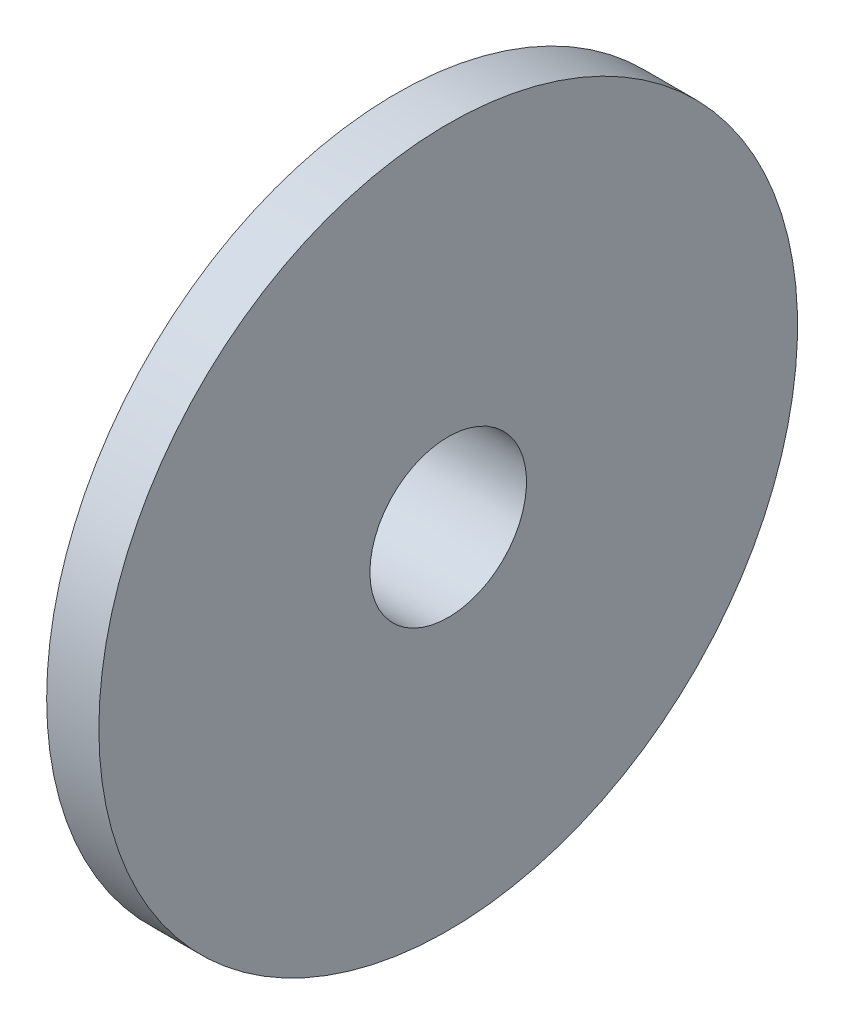
SolidWorks part; units mm, degrees
ref_plane "前视基准面" through (0, 0, 0) normal (0, 0, 1) x (1, 0, 0)
ref_plane "上视基准面" through (0, 0, 0) normal (0, 1, 0) x (1, 0, 0)
ref_plane "右视基准面" through (0, 0, 0) normal (1, 0, 0) x (0, 0, -1)
sketch "草图1" plane through (0, 0, 0) normal (0, 0, 1) x (1, 0, 0)
  line L0 (-9.1, 0) -> (4.0429, 0) construction
  line L1 (0, 9.1) -> (0, -7.5) construction
  line L2 (0, 1.5) -> (0, 6.6929)
  line L3 (0, 6.6929) -> (-1, 6.6929)
  line L4 (-1, 6.6929) -> (-1, 2.75)
  line L5 (-1, 2.75) -> (-3, 2.75)
  line L6 (-3, 2.75) -> (-3, 1.5)
  line L7 (-3, 1.5) -> (0, 1.5)
  dimension "D1" = 3
  dimension "D2" = 5.5
  dimension "D3" = 1
  dimension "D4" = 3
revolve "旋转1" add sketch "草图1" angle 360 about L0
chamfer "倒角1" distance 0.2 angle 45 2 edges at (-3, 0, 2.75) (-3, 0, 1.5)
